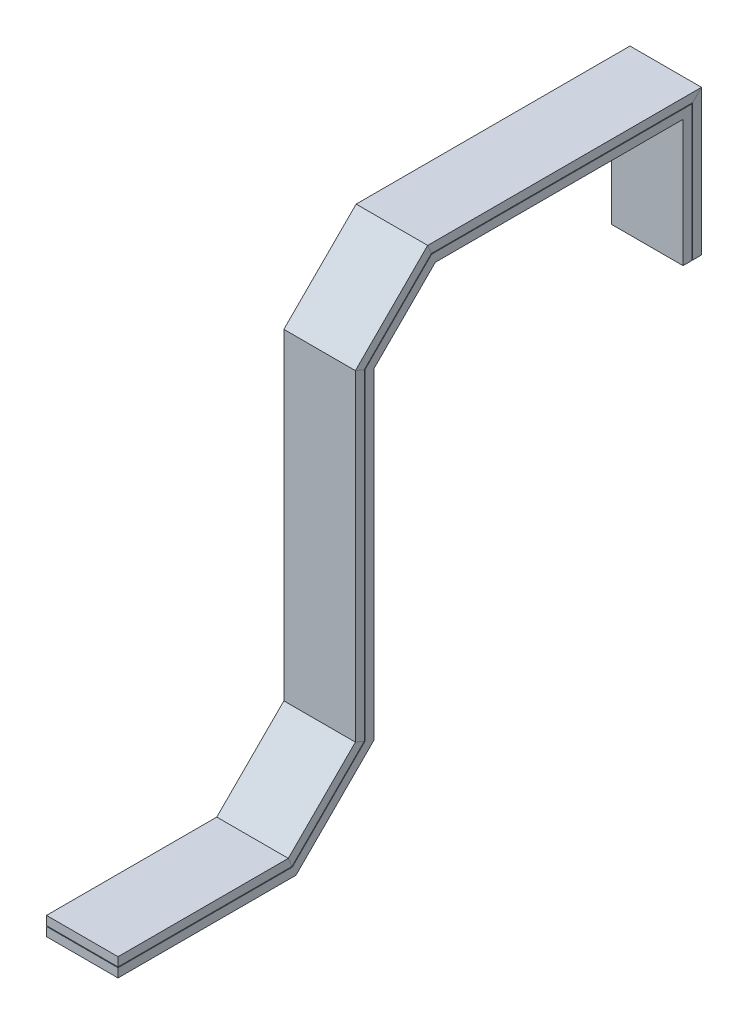
SolidWorks part; units mm, degrees
ref_plane "Alzado" through (0, 0, 0) normal (0, 0, 1) x (1, 0, 0)
ref_plane "Planta" through (0, 0, 0) normal (0, 1, 0) x (1, 0, 0)
ref_plane "Vista lateral" through (0, 0, 0) normal (1, 0, 0) x (0, 0, -1)
sketch "Croquis1" plane through (0, 0, 0) normal (0, 1, 0) x (1, 0, 0)
  line L1 (-25.4, 3.155) -> (25.4, 3.155)
  line L2 (-25.4, 3.155) -> (-25.4, -3.155)
  line L3 (-25.4, -3.155) -> (25.4, -3.155)
  line L4 (25.4, 3.155) -> (25.4, -3.155)
  line L5 (-25.4, 3.155) -> (25.4, -3.155) construction
  line L6 (-25.4, -3.155) -> (25.4, 3.155) construction
  point P0 (0, 0)
  dimension "D1" = 6.31
  dimension "D2" = 50.8
sketch3d "Croquis3D1"
  line L0 (0, 0, 0) -> (0, 100, 0)
  line L1 (0, 100, 0) -> (0, 100, 190)
  line L3 (0, 100, 190) -> (0, 50.5025, 239.4975)
  line L4 (0, 50.5025, 239.4975) -> (0, -178.0025, 239.4975)
  line L5 (0, -178.0025, 239.4975) -> (0, -227.5, 288.9949)
  line L7 (0, -227.5, 288.9949) -> (0, -227.5, 411.2249)
  dimension "D1" = 100
  dimension "D2" = 190
  dimension "D3" = 327.5
  dimension "D8" = 122.23
  dimension "D4" = 135
  dimension "D5" = 135
  dimension "D6" = 70
  dimension "D9" = 228.5051
  dimension "D7" = 70
sweep "Barrer1" add profiles "Croquis1" path "Croquis3D1"
sketch "Croquis2" plane through (-25.4, 0, 0) normal (-1, 0, 0) x (0, 0, 1)
  line L0 (3.155, 0) -> (3.155, 96.845) construction
  line L1 (3.155, 96.845) -> (188.6932, 96.845) construction
  line L2 (188.6932, 96.845) -> (236.3425, 49.1957) construction
  line L3 (236.3425, 49.1957) -> (236.3425, -179.3094) construction
  line L4 (236.3425, -179.3094) -> (287.6881, -230.655) construction
  line L5 (287.6881, -230.655) -> (411.2249, -230.655) construction
  line L6 (3.655, 0) -> (3.655, 96.345)
  line L7 (3.655, 96.345) -> (188.486, 96.345)
  line L8 (188.486, 96.345) -> (235.8425, 48.9886)
  line L9 (235.8425, 48.9886) -> (235.8425, -179.5165)
  line L10 (235.8425, -179.5165) -> (287.481, -231.155)
  line L11 (287.481, -231.155) -> (411.2249, -231.155)
  line L12 (9.965, 0) -> (9.965, 90.035)
  line L13 (9.965, 90.035) -> (185.8724, 90.035)
  line L14 (185.8724, 90.035) -> (229.5325, 46.3749)
  line L15 (229.5325, 46.3749) -> (229.5325, -182.1302)
  line L16 (229.5325, -182.1302) -> (284.8673, -237.465)
  line L17 (284.8673, -237.465) -> (411.2249, -237.465)
  line L18 (411.2249, -231.155) -> (411.2249, -237.465)
  line L19 (3.655, 0) -> (9.965, 0)
  dimension "D1" = 0.5
  dimension "D2" = 6.31
extrude "Saliente-Extruir1" add sketch "Croquis2" against normal blind 50.8 separate body
